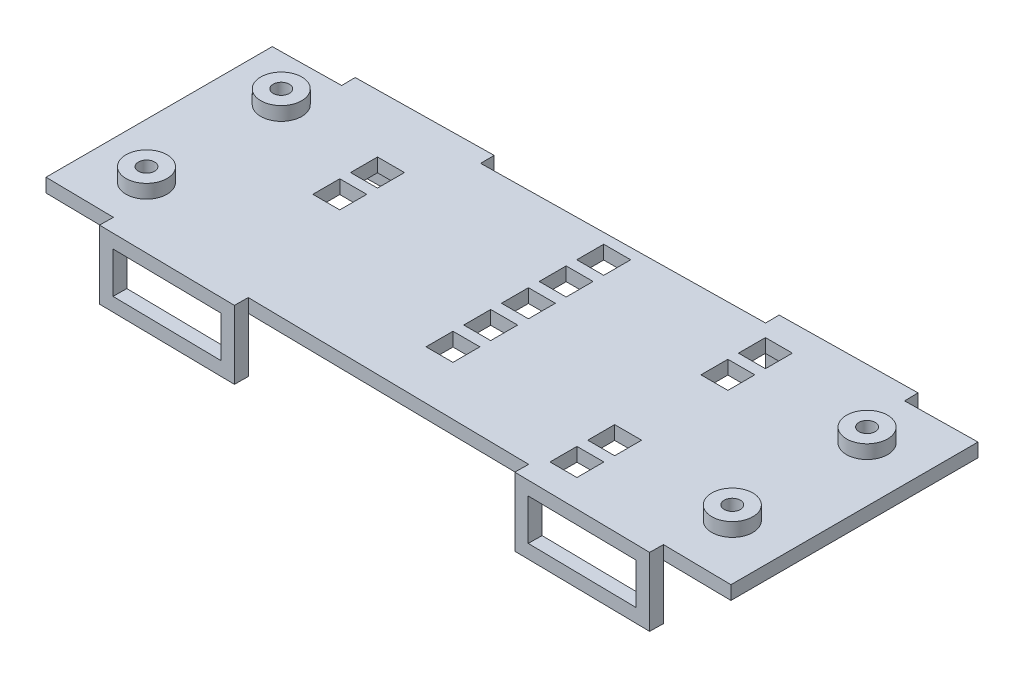
SolidWorks part; units mm, degrees
ref_plane "Front Plane" through (0, 0, 0) normal (0, 0, 1) x (1, 0, 0)
ref_plane "Top Plane" through (0, 0, 0) normal (0, 1, 0) x (1, 0, 0)
ref_plane "Right Plane" through (0, 0, 0) normal (1, 0, 0) x (0, 0, -1)
sketch "Sketch2" plane through (0, 0, 0) normal (0, 1, 0) x (1, 0, 0)
  line L9 (-79.1839, 4.616) -> (47.8161, 4.616) construction
  line L10 (21.1386, 26.1208) -> (20.4936, -16.8792) construction
  line L13 (-80.1839, 25.6011) -> (48.8161, 27.5361)
  line L14 (48.8161, 27.5361) -> (48.8161, -18.3042)
  line L15 (48.8161, -18.3042) -> (-80.1839, -16.3692)
  line L16 (-80.1839, -16.3692) -> (-80.1839, 25.6011)
  point P2 (-79.1839, 4.616)
  point P5 (47.8161, 4.616)
  point P10 (20.8161, 4.6208)
  dimension "D1" = 41.9702
  dimension "D3" = 127
  dimension "D4" = 43
extrude "Boss-Extrude1" add sketch "Sketch2" along normal blind 2.54
sketch "Sketch3" plane through (0.0467, 0, 17.5726) normal (-0.015, 0, 0.9999) x (0.9999, 0, 0.015)
  line L1 (-67.5396, 2.54) -> (-42.1396, 2.54)
  line L2 (-67.5396, 2.54) -> (-67.5396, -10.16)
  line L3 (-67.5396, -10.16) -> (-42.1396, -10.16)
  line L4 (-42.1396, 2.54) -> (-42.1396, -10.16)
  line L5 (-64.9996, 0) -> (-64.9996, -7.62)
  line L6 (-64.9996, -7.62) -> (-44.6796, -7.62)
  line L7 (-44.6796, 0) -> (-44.6796, -7.62)
  line L8 (-64.9996, 0) -> (-44.6796, 0)
  line L9 (10.6749, 2.54) -> (36.0749, 2.54)
  line L10 (10.6749, 2.54) -> (10.6749, -10.16)
  line L11 (10.6749, -10.16) -> (36.0749, -10.16)
  line L12 (36.0749, 2.54) -> (36.0749, -10.16)
  line L13 (13.2149, 0) -> (13.2149, -7.62)
  line L14 (13.2149, -7.62) -> (33.5349, -7.62)
  line L15 (33.5349, 0) -> (33.5349, -7.62)
  line L16 (13.2149, 0) -> (33.5349, 0)
  line L20 (-80.2396, 2.54) -> (-80.2396, 0) construction
  line L21 (48.7749, 2.54) -> (48.7749, 0) construction
  point P4 (0, 0)
  dimension "D1" = 12.7
  dimension "D2" = 25.4
  dimension "D3" = 12.7
  dimension "D6" = 2.54
  dimension "D7" = 20.32
  dimension "D8" = 25.4
  dimension "D9" = 12.7
  dimension "D4" = 12.7
extrude "Boss-Extrude3" add sketch "Sketch3" along normal blind 2.54
sketch "Sketch4" plane through (0, 0, 0) normal (0, -1, 0) x (1, 0, 0)
  line L4 (-80.1839, -25.6011) -> (-80.1839, 16.3692) construction
  line L7 (-80.1839, 16.3692) -> (-67.4853, 16.5596) construction
  line L8 (48.8161, -27.5361) -> (-80.1839, -25.6011) construction
  line L9 (36.1176, 18.1137) -> (48.8161, 18.3042) construction
  line L10 (48.8161, 18.3042) -> (48.8161, -27.5361) construction
  circle A0 centre (-72.5639, 8.9826) radius 1.905
  circle A1 centre (-72.1839, -18.2202) radius 1.905
  circle A2 centre (41.1961, -19.9209) radius 1.905
  circle A3 centre (41.1961, 10.689) radius 1.905
  point P10 (-65.7926, 10.3127)
  point P11 (0, 0)
  point P16 (37.6207, 6.0192)
  point P17 (37.6207, -15.0284)
  dimension "D1" = 3.81
  dimension "D2" = 7.62
  dimension "D3" = 7.5
  dimension "D4" = 7.5
  dimension "D5" = 7.5
  dimension "D6" = 7.5
  dimension "D7" = 7.62
  dimension "D8" = 7.62
extrude "Boss-Extrude4" add sketch "Sketch4" along normal blind 5.08
sketch "Sketch5" plane through (0, 2.54, 0) normal (0, 1, 0) x (1, 0, 0)
  line L1 (-80.1839, 25.6011) -> (-80.1839, -16.3692) construction
  line L2 (48.8161, -18.3042) -> (48.8161, 27.5361) construction
  circle A2 centre (-70.0239, 17.116) radius 1.5
  circle A3 centre (-70.0239, -7.884) radius 1.5
  circle A5 centre (38.6561, 17.116) radius 1.5
  circle A6 centre (-70.0239, 17.116) radius 3.81
  circle A7 centre (-70.0239, -7.884) radius 3.81
  circle A8 centre (38.6561, -7.884) radius 3.81
  circle A9 centre (38.6561, 17.116) radius 3.81
  circle A10 centre (38.6561, -7.884) radius 1.5
  dimension "D2" = 3
  dimension "D4" = 7.62
  dimension "D5" = 10.16
  dimension "D1" = 25
  dimension "D3" = 25
  dimension "D6" = 10.16
extrude "Boss-Extrude5" add sketch "Sketch5" along normal blind 2.54
sketch "Sketch6" plane through (-0.402, 0, -26.7978) normal (-0.015, 0, -0.9999) x (-0.9999, 0, 0.015)
  line L0 (-49.2236, 2.54) -> (79.7909, 2.54) construction
  line L1 (-35.7973, 2.54) -> (-10.3973, 2.54)
  line L2 (-35.7973, 2.54) -> (-35.7973, -10.16)
  line L3 (-35.7973, -10.16) -> (-10.3973, -10.16)
  line L4 (-10.3973, 2.54) -> (-10.3973, -10.16)
  line L5 (-49.2236, 2.54) -> (-49.2236, 0) construction
  line L11 (79.7909, 2.54) -> (79.7909, 0) construction
  line L12 (41.6909, 2.54) -> (67.0909, 2.54)
  line L13 (41.6909, 2.54) -> (41.6909, -10.16)
  line L14 (41.6909, -10.16) -> (67.0909, -10.16)
  line L15 (67.0909, 2.54) -> (67.0909, -10.16)
  line L16 (-12.9373, 0) -> (-12.9373, -7.62)
  line L17 (-33.2573, -7.62) -> (-12.9373, -7.62)
  line L18 (-33.2573, 0) -> (-33.2573, -7.62)
  line L19 (-33.2573, 0) -> (-12.9373, 0)
  line L20 (44.2309, -7.62) -> (64.5509, -7.62)
  line L21 (64.5509, 0) -> (64.5509, -7.62)
  line L22 (44.2309, 0) -> (64.5509, 0)
  line L23 (44.2309, 0) -> (44.2309, -7.62)
  dimension "D1" = 13.4264
  dimension "D2" = 12.7
  dimension "D3" = 12.7
  dimension "D4" = 25.4
  dimension "D5" = 12.7
  dimension "D6" = 25.4
  dimension "D7" = 2.54
extrude "Boss-Extrude8" add sketch "Sketch6" along normal blind 2.54
sketch "Sketch1" [suppressed] plane through (0, 2.54, 0) normal (0, 1, 0) x (1, 0, 0)
  line L0 (-74.5, -10.5) -> (74.5, -10.5) construction
  line L1 (-74.5, -17.5) -> (74.5, -17.5) construction
  line L2 (-74.5, -17.5) -> (-74.5, 17.5) construction
  line L3 (-74.5, 17.5) -> (74.5, 17.5) construction
  line L4 (74.5, -17.5) -> (74.5, 17.5) construction
  line L5 (-74.5, -17.5) -> (74.5, 17.5) construction
  line L6 (-74.5, 17.5) -> (74.5, -17.5) construction
  line L7 (-74.5, 10.5) -> (74.5, 10.5) construction
  line L8 (-74.5, -3.5) -> (74.5, -3.5) construction
  line L9 (-74.5, 3.5) -> (74.5, 3.5) construction
  line L10 (-39.5, 17.5) -> (-39.5, -17.5) construction
  line L11 (-4.5, -17.5) -> (-4.5, 17.5) construction
  line L12 (25.5, -17.5) -> (25.5, 17.5) construction
  line L13 (55.5, 17.5) -> (55.5, -17.5) construction
  line L15 (-47.675, 7.325) -> (-41.325, 7.325)
  line L16 (-47.675, 0.325) -> (-41.325, 0.325)
  line L17 (-47.675, 0.325) -> (-47.675, 6.675)
  line L18 (-47.675, 6.675) -> (-41.325, 6.675)
  line L19 (-41.325, 0.325) -> (-41.325, 6.675)
  line L20 (-47.675, 0.325) -> (-41.325, 6.675) construction
  line L21 (-47.675, 6.675) -> (-41.325, 0.325) construction
  line L22 (-47.675, 7.325) -> (-47.675, 13.675)
  line L23 (-47.675, 13.675) -> (-41.325, 13.675)
  line L24 (-41.325, 7.325) -> (-41.325, 13.675)
  line L25 (-47.675, 7.325) -> (-41.325, 13.675) construction
  line L26 (-47.675, 13.675) -> (-41.325, 7.325) construction
  line L27 (-12.675, -13.675) -> (-6.325, -13.675)
  line L28 (-12.675, -13.675) -> (-12.675, -7.325)
  line L29 (-12.675, -7.325) -> (-6.325, -7.325)
  line L30 (-6.325, -13.675) -> (-6.325, -7.325)
  line L31 (-12.675, -13.675) -> (-6.325, -7.325) construction
  line L32 (-12.675, -7.325) -> (-6.325, -13.675) construction
  line L33 (-12.675, -6.675) -> (-6.325, -6.675)
  line L34 (-12.675, -6.675) -> (-12.675, -0.325)
  line L35 (-12.675, -0.325) -> (-6.325, -0.325)
  line L36 (-6.325, -6.675) -> (-6.325, -0.325)
  line L37 (-12.675, -6.675) -> (-6.325, -0.325) construction
  line L38 (-12.675, -0.325) -> (-6.325, -6.675) construction
  line L39 (-12.675, 0.325) -> (-6.325, 0.325)
  line L40 (-12.675, 0.325) -> (-12.675, 6.675)
  line L41 (-12.675, 6.675) -> (-6.325, 6.675)
  line L42 (-6.325, 0.325) -> (-6.325, 6.675)
  line L43 (-12.675, 0.325) -> (-6.325, 6.675) construction
  line L44 (-12.675, 6.675) -> (-6.325, 0.325) construction
  line L45 (-12.675, 7.325) -> (-6.325, 7.325)
  line L46 (-12.675, 7.325) -> (-12.675, 13.675)
  line L47 (-12.675, 13.675) -> (-6.325, 13.675)
  line L48 (-6.325, 7.325) -> (-6.325, 13.675)
  line L49 (-12.675, 7.325) -> (-6.325, 13.675) construction
  line L50 (-12.675, 13.675) -> (-6.325, 7.325) construction
  line L51 (-12.675, 14.325) -> (-6.325, 14.325)
  line L52 (-12.675, 14.325) -> (-12.675, 20.675)
  line L53 (-12.675, 20.675) -> (-6.325, 20.675)
  line L54 (-6.325, 14.325) -> (-6.325, 20.675)
  line L55 (-12.675, 14.325) -> (-6.325, 20.675) construction
  line L56 (-12.675, 20.675) -> (-6.325, 14.325) construction
  line L57 (17.325, -20.675) -> (23.675, -20.675)
  line L58 (17.325, -20.675) -> (17.325, -14.325)
  line L59 (17.325, -14.325) -> (23.675, -14.325)
  line L60 (23.675, -20.675) -> (23.675, -14.325)
  line L61 (17.325, -20.675) -> (23.675, -14.325) construction
  line L62 (17.325, -14.325) -> (23.675, -20.675) construction
  line L63 (17.325, -13.675) -> (23.675, -13.675)
  line L64 (17.325, -13.675) -> (17.325, -7.325)
  line L65 (17.325, -7.325) -> (23.675, -7.325)
  line L66 (23.675, -13.675) -> (23.675, -7.325)
  line L67 (17.325, -13.675) -> (23.675, -7.325) construction
  line L68 (17.325, -7.325) -> (23.675, -13.675) construction
  line L69 (17.325, 7.325) -> (23.675, 7.325)
  line L70 (17.325, 7.325) -> (17.325, 13.675)
  line L71 (17.325, 13.675) -> (23.675, 13.675)
  line L72 (23.675, 7.325) -> (23.675, 13.675)
  line L73 (17.325, 7.325) -> (23.675, 13.675) construction
  line L74 (17.325, 13.675) -> (23.675, 7.325) construction
  line L75 (17.325, 14.325) -> (23.675, 14.325)
  line L76 (17.325, 14.325) -> (17.325, 20.675)
  line L77 (17.325, 20.675) -> (23.675, 20.675)
  line L78 (23.675, 14.325) -> (23.675, 20.675)
  line L79 (17.325, 14.325) -> (23.675, 20.675) construction
  line L80 (17.325, 20.675) -> (23.675, 14.325) construction
  point P0 (0, 0)
  point P22 (-9.5, -10.5)
  point P23 (-44.5, 3.5)
  point P29 (-44.5, 10.5)
  point P37 (-9.5, -3.5)
  point P42 (-9.5, 3.5)
  point P47 (-9.5, 10.5)
  point P52 (-9.5, 17.5)
  point P57 (20.5, -17.5)
  point P62 (20.5, -10.5)
  point P67 (20.5, 10.5)
  point P72 (20.5, 17.5)
  point P77 (0, 0)
  point P78 (0, 0)
  point P79 (0, 0)
  point P82 (0, 0)
  dimension "D2" = 7
  dimension "D3" = 7
  dimension "D4" = 7
  dimension "D5" = 7
  dimension "D6" = 7
  dimension "D7" = 35
  dimension "D8" = 35
  dimension "D9" = 30
  dimension "D10" = 30
  dimension "D11" = 19
  dimension "D12" = 6.35
  dimension "D13" = 25
  dimension "D14" = 30
  dimension "D15" = 30
sketch "Sketch12" plane through (0, 2.54, 0) normal (0, 1, 0) x (1, 0, 0)
  line L0 (-80.1839, 25.6011) -> (-80.1839, -16.3692) construction
  line L1 (-45.1839, 26.1261) -> (-45.1839, -16.8942) construction
  line L2 (-80.1839, -12.8688) -> (30.6127, -12.8688) construction
  line L3 (-80.1839, 22.1007) -> (30.6127, 22.1007) construction
  line L4 (9.9941, 26.9537) -> (-42.0882, 26.1725) construction
  line L5 (-42.0882, -16.9406) -> (10.7204, -17.7327) construction
  line L6 (-10.1839, 26.6511) -> (-10.1839, -16.3692) construction
  line L7 (19.8161, 26.6511) -> (19.8161, -16.3692) construction
  line L8 (-67.4853, 25.7915) -> (-80.1839, 25.6011) construction
  line L9 (-80.1839, -16.3692) -> (-67.4853, -16.5596) construction
  line L10 (-80.1839, 15.1312) -> (33.1526, 15.1312) construction
  line L11 (-80.1839, 8.1312) -> (30.6127, 8.1312) construction
  line L12 (-80.1839, 1.1312) -> (30.6127, 1.1312) construction
  line L13 (-80.1839, -5.8688) -> (30.6127, -5.8688) construction
  line L15 (-52.6839, 12.6312) -> (-47.6839, 12.6312)
  line L16 (-52.6839, 12.6312) -> (-52.6839, 17.6312)
  line L17 (-52.6839, 17.6312) -> (-47.6839, 17.6312)
  line L18 (-47.6839, 12.6312) -> (-47.6839, 17.6312)
  line L19 (-52.6839, 12.6312) -> (-47.6839, 17.6312) construction
  line L20 (-52.6839, 17.6312) -> (-47.6839, 12.6312) construction
  line L21 (-52.6839, 5.6312) -> (-47.6839, 5.6312)
  line L22 (-52.6839, 5.6312) -> (-52.6839, 10.6312)
  line L23 (-52.6839, 10.6312) -> (-47.6839, 10.6312)
  line L24 (-47.6839, 5.6312) -> (-47.6839, 10.6312)
  line L25 (-52.6839, 5.6312) -> (-47.6839, 10.6312) construction
  line L26 (-52.6839, 10.6312) -> (-47.6839, 5.6312) construction
  line L27 (-17.6839, 19.6007) -> (-12.6839, 19.6007)
  line L28 (-17.6839, 19.6007) -> (-17.6839, 24.6007)
  line L29 (-17.6839, 24.6007) -> (-12.6839, 24.6007)
  line L30 (-12.6839, 19.6007) -> (-12.6839, 24.6007)
  line L31 (-17.6839, 19.6007) -> (-12.6839, 24.6007) construction
  line L32 (-17.6839, 24.6007) -> (-12.6839, 19.6007) construction
  line L33 (-17.6839, 12.6312) -> (-12.6839, 12.6312)
  line L34 (-17.6839, 12.6312) -> (-17.6839, 17.6312)
  line L35 (-17.6839, 17.6312) -> (-12.6839, 17.6312)
  line L36 (-12.6839, 12.6312) -> (-12.6839, 17.6312)
  line L37 (-17.6839, 12.6312) -> (-12.6839, 17.6312) construction
  line L38 (-17.6839, 17.6312) -> (-12.6839, 12.6312) construction
  line L39 (-17.6839, 5.6312) -> (-12.6839, 5.6312)
  line L40 (-17.6839, 5.6312) -> (-17.6839, 10.6312)
  line L41 (-17.6839, 10.6312) -> (-12.6839, 10.6312)
  line L42 (-12.6839, 5.6312) -> (-12.6839, 10.6312)
  line L43 (-17.6839, 5.6312) -> (-12.6839, 10.6312) construction
  line L44 (-17.6839, 10.6312) -> (-12.6839, 5.6312) construction
  line L45 (-17.6839, -1.3688) -> (-12.6839, -1.3688)
  line L46 (-17.6839, -1.3688) -> (-17.6839, 3.6312)
  line L47 (-17.6839, 3.6312) -> (-12.6839, 3.6312)
  line L48 (-12.6839, -1.3688) -> (-12.6839, 3.6312)
  line L49 (-17.6839, -1.3688) -> (-12.6839, 3.6312) construction
  line L50 (-17.6839, 3.6312) -> (-12.6839, -1.3688) construction
  line L51 (-17.6839, -8.3688) -> (-12.6839, -8.3688)
  line L52 (-17.6839, -8.3688) -> (-17.6839, -3.3688)
  line L53 (-17.6839, -3.3688) -> (-12.6839, -3.3688)
  line L54 (-12.6839, -8.3688) -> (-12.6839, -3.3688)
  line L55 (-17.6839, -8.3688) -> (-12.6839, -3.3688) construction
  line L56 (-17.6839, -3.3688) -> (-12.6839, -8.3688) construction
  line L57 (12.3161, -15.3688) -> (17.3161, -15.3688)
  line L58 (12.3161, -15.3688) -> (12.3161, -10.3688)
  line L59 (12.3161, -10.3688) -> (17.3161, -10.3688)
  line L60 (17.3161, -15.3688) -> (17.3161, -10.3688)
  line L61 (12.3161, -15.3688) -> (17.3161, -10.3688) construction
  line L62 (12.3161, -10.3688) -> (17.3161, -15.3688) construction
  line L63 (12.3161, -8.3688) -> (17.3161, -8.3688)
  line L64 (12.3161, -8.3688) -> (12.3161, -3.3688)
  line L65 (12.3161, -3.3688) -> (17.3161, -3.3688)
  line L66 (17.3161, -8.3688) -> (17.3161, -3.3688)
  line L67 (12.3161, -8.3688) -> (17.3161, -3.3688) construction
  line L68 (12.3161, -3.3688) -> (17.3161, -8.3688) construction
  line L69 (12.3161, 19.6007) -> (17.3161, 19.6007)
  line L70 (12.3161, 19.6007) -> (12.3161, 24.6007)
  line L71 (12.3161, 24.6007) -> (17.3161, 24.6007)
  line L72 (17.3161, 19.6007) -> (17.3161, 24.6007)
  line L73 (12.3161, 19.6007) -> (17.3161, 24.6007) construction
  line L74 (12.3161, 24.6007) -> (17.3161, 19.6007) construction
  line L75 (12.3161, 12.6312) -> (17.3161, 12.6312)
  line L76 (12.3161, 12.6312) -> (12.3161, 17.6312)
  line L77 (12.3161, 17.6312) -> (17.3161, 17.6312)
  line L78 (17.3161, 12.6312) -> (17.3161, 17.6312)
  line L79 (12.3161, 12.6312) -> (17.3161, 17.6312) construction
  line L80 (12.3161, 17.6312) -> (17.3161, 12.6312) construction
  point P30 (-50.1839, 15.1312)
  point P35 (-50.1839, 8.1312)
  point P40 (-15.1839, 15.1312)
  point P41 (-15.1839, 22.1007)
  point P50 (-15.1839, 8.1312)
  point P55 (-15.1839, 1.1312)
  point P60 (-15.1839, -5.8688)
  point P65 (14.8161, -5.8688)
  point P66 (14.8161, -12.8688)
  point P75 (14.8161, 22.1007)
  point P80 (14.8161, 15.1312)
  point P85 (0, 0)
  dimension "D1" = 35
  dimension "D2" = 35
  dimension "D3" = 30
  dimension "D4" = 3.5
  dimension "D5" = 3.5
  dimension "D6" = 7
  dimension "D7" = 7
  dimension "D8" = 7
  dimension "D9" = 7
  dimension "D10" = 5
  dimension "D11" = 5
  dimension "D12" = 5
  dimension "D13" = 5
  dimension "D14" = 5
  dimension "D15" = 5
extrude "Cut-Extrude1" cut sketch "Sketch12" against normal blind 2.54
